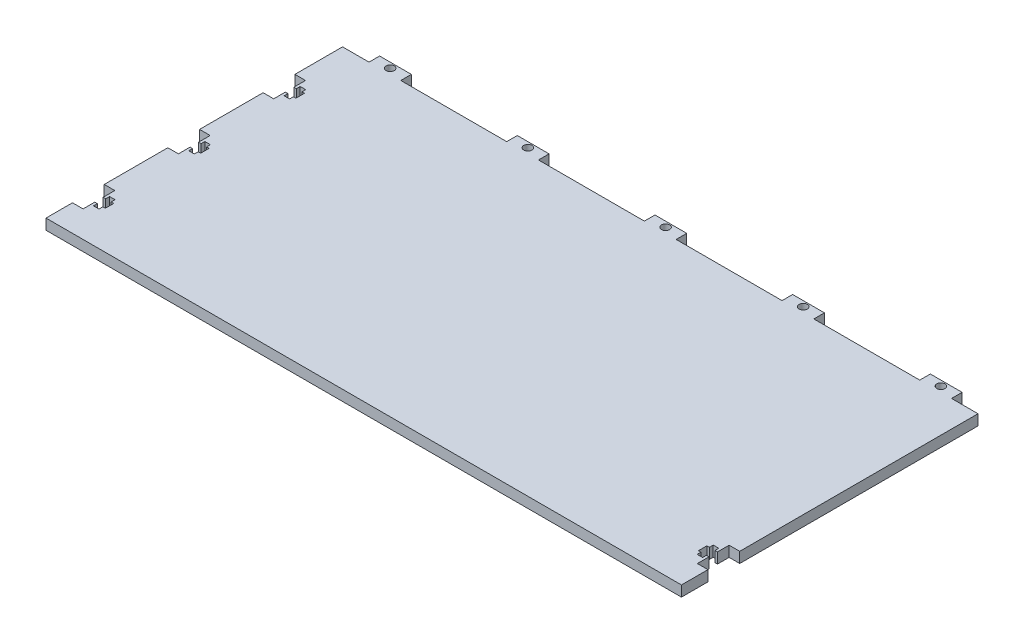
SolidWorks part; units mm, degrees
ref_plane "Front Plane" through (0, 0, 0) normal (0, 0, 1) x (1, 0, 0)
ref_plane "Top Plane" through (0, 0, 0) normal (0, 1, 0) x (1, 0, 0)
ref_plane "Right Plane" through (0, 0, 0) normal (1, 0, 0) x (0, 0, -1)
sketch "Sketch1" plane through (0, 0, 0) normal (0, 1, 0) x (1, 0, 0)
  line L1 (0, 0) -> (381, 0)
  line L2 (0, 0) -> (0, 177.8)
  line L3 (0, 177.8) -> (381, 177.8)
  line L4 (381, 0) -> (381, 177.8)
  dimension "D1" = 381
  dimension "D2" = 177.8
extrude "Boss-Extrude1" add sketch "Sketch1" along normal blind 6.35
sketch "Sketch2" plane through (0, 6.35, 0) normal (0, 1, 0) x (1, 0, 0)
  line L0 (381, 177.8) -> (0, 177.8) construction
  line L1 (15.875, 177.8) -> (34.925, 177.8)
  line L2 (15.875, 177.8) -> (15.875, 184.15)
  line L3 (15.875, 184.15) -> (34.925, 184.15)
  line L4 (34.925, 177.8) -> (34.925, 184.15)
  line L5 (0, 177.8) -> (0, 0) construction
  dimension "D1" = 19.05
  dimension "D2" = 6.35
  dimension "D3" = 15.875
extrude "Boss-Extrude2" add sketch "Sketch2" against normal blind 6.35
hole_wizard "#10 (0.1935) Diameter Hole1" positions "Sketch5" profile "Sketch4" hole size "#10" standard "ANSI Inch" end condition through all
sketch "Sketch5" plane through (0, 6.35, 0) normal (0, 1, 0) x (1, 0, 0)
  line L2 (15.875, 180.975) -> (34.925, 180.975) construction
  line L3 (15.875, 184.15) -> (15.875, 177.8) construction
  line L4 (34.925, 177.8) -> (34.925, 184.15) construction
  point P0 (25.4, 180.975)
sketch "Sketch4" plane through (25.4, 6.35, -180.975) normal (1, 0, 0) x (0, 0, 1)
  line L0 (0, 0) -> (0, 6.35)
  line L1 (0, 6.35) -> (2.4574, 6.35)
  line L2 (2.4574, 6.35) -> (2.4574, 0)
  line L5 (2.4574, 0) -> (0, 0)
  line L11 (0, -6.35) -> (0, 107.95) construction
  dimension "Thru Hole Dia." = 4.9149
  dimension "Thru Hole Depth" = 6.35
pattern_linear "LPattern1" count 5 spacing 82.55 along (1, 0, 0) of "#10 (0.1935) Diameter Hole1", "Boss-Extrude2"
sketch "Sketch7" plane through (0, 6.35, 0) normal (0, 1, 0) x (1, 0, 0)
  line L0 (0, 34.925) -> (0, 15.875)
  line L1 (0, 34.925) -> (6.35, 34.925)
  line L2 (6.35, 34.925) -> (6.35, 27.94)
  line L3 (0, 15.875) -> (6.35, 15.875)
  line L4 (6.35, 27.94) -> (7.874, 27.94)
  line L5 (12.7, 27.94) -> (12.7, 22.86)
  line L6 (6.35, 22.86) -> (7.874, 22.86)
  line L7 (11.176, 27.94) -> (12.7, 27.94)
  line L8 (11.176, 30.226) -> (11.176, 27.94)
  line L9 (11.176, 30.226) -> (7.874, 30.226)
  line L10 (7.874, 30.226) -> (7.874, 27.94)
  line L11 (11.176, 20.574) -> (7.874, 20.574)
  line L12 (11.176, 22.86) -> (11.176, 20.574)
  line L13 (11.176, 22.86) -> (12.7, 22.86)
  line L14 (7.874, 22.86) -> (7.874, 20.574)
  line L15 (6.35, 22.86) -> (6.35, 15.875)
  line L16 (0, 177.8) -> (0, 0) construction
  line L17 (15.875, 177.8) -> (0, 177.8) construction
  point P8 (12.7, 25.4)
  dimension "D1" = 6.35
  dimension "D2" = 5.08
  dimension "D3" = 6.35
  dimension "D4" = 9.652
  dimension "D5" = 3.302
  dimension "D6" = 19.05
  dimension "D7" = 142.875
extrude "Cut-Extrude2" cut sketch "Sketch7" against normal through all
ref_plane "Plane2" through (190.5, 0, 0) normal (-1, 0, 0) x (0, 0, 1)
mirror "Mirror2" about plane through (190.5, 0, 0) normal (-1, 0, 0) of "Cut-Extrude2"
pattern_linear "LPattern4" count 3 spacing 57.15 along (0, 0, -1) of "Cut-Extrude2"
